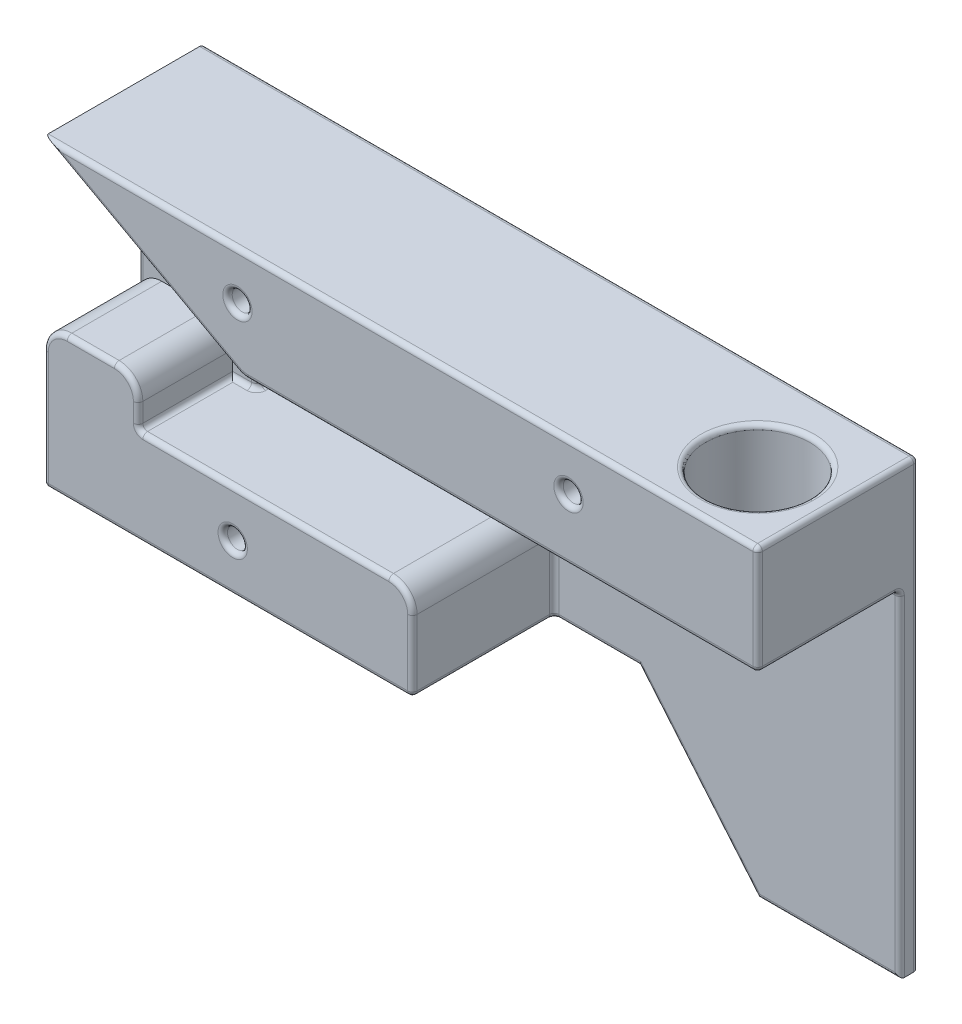
SolidWorks part; units mm, degrees
ref_plane "Front Plane" through (0, 0, 0) normal (0, 0, 1) x (1, 0, 0)
ref_plane "Top Plane" through (0, 0, 0) normal (0, 1, 0) x (1, 0, 0)
ref_plane "Right Plane" through (0, 0, 0) normal (1, 0, 0) x (0, 0, -1)
sketch "Sketch1" plane through (0, 0, 0) normal (0, 0, 1) x (1, 0, 0)
  line L0 (95.827, 0) -> (121, -30)
  line L1 (0, 0) -> (95.827, 0)
  line L2 (0, 0) -> (0, 64)
  line L3 (0, 64) -> (151, 64)
  line L4 (151, -30) -> (151, 64)
  line L5 (121, -30) -> (151, -30)
  dimension "D1" = 64
  dimension "D2" = 151
  dimension "D3" = 30
  dimension "D4" = 30
  dimension "D5" = 130
extrude "Boss-Extrude1" add sketch "Sketch1" along normal blind 4
sketch "Sketch2" plane through (0, 0, 4) normal (0, 0, 1) x (1, 0, 0)
  line L0 (0, 64) -> (151, 64)
  line L1 (151, 64) -> (151, 41)
  line L2 (151, -30) -> (151, 64) construction
  line L3 (151, 41) -> (42, 41)
  line L4 (42, 41) -> (0, 64)
  line L6 (20, 20) -> (20, 30)
  line L7 (20, 30) -> (0, 30)
  line L8 (0, 64) -> (0, 0) construction
  line L9 (0, 30) -> (0, 0)
  line L12 (20, 20) -> (78, 20)
  line L13 (78, 20) -> (78, 0)
  line L14 (0, 0) -> (95.827, 0) construction
  line L15 (78, 0) -> (0, 0)
  dimension "D1" = 23
  dimension "D2" = 42
  dimension "D3" = 20
  dimension "D4" = 10
  dimension "D5" = 20
  dimension "D6" = 78
extrude "Boss-Extrude2" add sketch "Sketch2" along normal blind 30
sketch "Sketch3" plane through (0, 0, 4) normal (0, 0, 1) x (1, 0, 0)
  line L0 (25, 20) -> (25, 50.3095)
  line L1 (78, 20) -> (20, 20) construction
  line L2 (0, 64) -> (42, 41) construction
  line L3 (25, 50.3095) -> (0, 64)
  line L4 (0, 64) -> (0, 30)
  line L5 (0, 30) -> (20, 30)
  line L6 (20, 30) -> (20, 20)
  line L7 (20, 20) -> (25, 20)
  dimension "D1" = 25
extrude "Boss-Extrude3" add sketch "Sketch3" along normal blind 10
sketch "Sketch4" plane through (0, 0, 4) normal (0, 0, 1) x (1, 0, 0)
  line L0 (25, 50.3095) -> (42, 41)
  line L1 (42, 41) -> (69, 41)
  line L2 (42, 41) -> (151, 41) construction
  line L3 (69, 41) -> (69, 20)
  line L4 (78, 20) -> (25, 20) construction
  line L5 (69, 20) -> (25, 20)
  line L6 (25, 20) -> (25, 50.3095)
  dimension "D1" = 44
extrude "Boss-Extrude4" add sketch "Sketch4" along normal blind 5
fillet "Fillet1" radius 5 4 edges at (20, 30, 24) (78, 20, 19) (42, 41, 21.5) (0, 30, 24)
sketch "Sketch5" plane through (0, 64, 0) normal (0, 1, 0) x (1, 0, 0)
  line L0 (151, -34) -> (151, -4) construction
  line L2 (0, -14) -> (0, 0) construction
  circle A0 centre (136, -19) radius 11
  point P5 (151, -19)
  dimension "D1" = 22
  dimension "D2" = 136
extrude "Cut-Extrude1" cut sketch "Sketch5" against normal up to next
hole_wizard "M5 Tapped Hole1" positions "Sketch8" profile "Sketch9" tap size "M5" standard "ISO"
sketch "Sketch8" plane through (0, 0, 34) normal (0, 0, 1) x (1, 0, 0)
  line L2 (151, 41) -> (151, 64) construction
  line L3 (151, 64) -> (0, 64) construction
  line L4 (0, 0) -> (78, 0) construction
  line L6 (0, 25) -> (0, 0) construction
  point P0 (41, 54)
  point P2 (111, 54)
  point P4 (40, 10)
  dimension "D1" = 70
  dimension "D2" = 40
  dimension "D3" = 10
  dimension "D4" = 10
  dimension "D5" = 40
sketch "Sketch9" plane through (41, 54, 34) normal (1, 0, 0) x (0, -1, 0)
  line L0 (0, 0) -> (0, 13.6618)
  line L1 (0, 13.6618) -> (2.1, 12.4)
  line L2 (2.1, 12.4) -> (2.1, 0)
  line L5 (2.1, 0) -> (0, 0)
  line L10 (0, 13.6618) -> (-2.1, 12.4) construction
  line L11 (0, -6.35) -> (0, 107.95) construction
  dimension "Tap Drill Dia." = 4.2
  dimension "Tap Drill Depth" = 12.4
  dimension "Drill Angle" = 118
cosmetic thread "Hole Thread1" parameters "D1"=10, "D2"=5
cosmetic thread "Hole Thread2" parameters "D1"=10, "D2"=5
cosmetic thread "Hole Thread3" parameters "D1"=10, "D2"=5
fillet "Fillet3" radius 1 51 edges at (151, 41, 19) (20, 20, 24) (22.5, 20, 14) (25, 20, 11.5) (32.9389, 45.962, 9) (42.0399, 41.1561, 9) (56.1397, 41, 9) (47, 20, 9) (25, 35.1548, 9) (110, 41, 4) (151, 5.5, 4) (136, -30, 4) (108.4135, -15, 4) (86.9135, 0, 4) (76.5355, 18.5355, 4) (71, 20, 4) (69, 20, 6.5) (69, 30.5, 9) (69, 41, 6.5) (69, 30.5, 4) (75.5, 64, 34) (151, 52.5, 34) (97.1397, 41, 34) (42.0399, 41.1561, 34) (20.4389, 52.8073, 34) (113.1, 54, 34) (43.1, 54, 34) (39, 0, 34) (0, 12.5, 34) (1.4645, 28.5355, 34) (10, 30, 34) (18.5355, 28.5355, 34) (20, 22.5, 34) (46.5, 20, 34) (76.5355, 18.5355, 34) (42.1, 10, 34) (78, 0, 19) (78, 7.5, 34) (78, 7.5, 4) (47.9135, 0, 0) (108.4135, -15, 0) (136, -30, 0) (151, 17, 0) (75.5, 64, 0) (0, 32, 0) (0, 0, 17) (125, 41, 19) (136, 64, 30) (151, 64, 17) (0, 44.5, 14) (25, 35.1548, 14)
